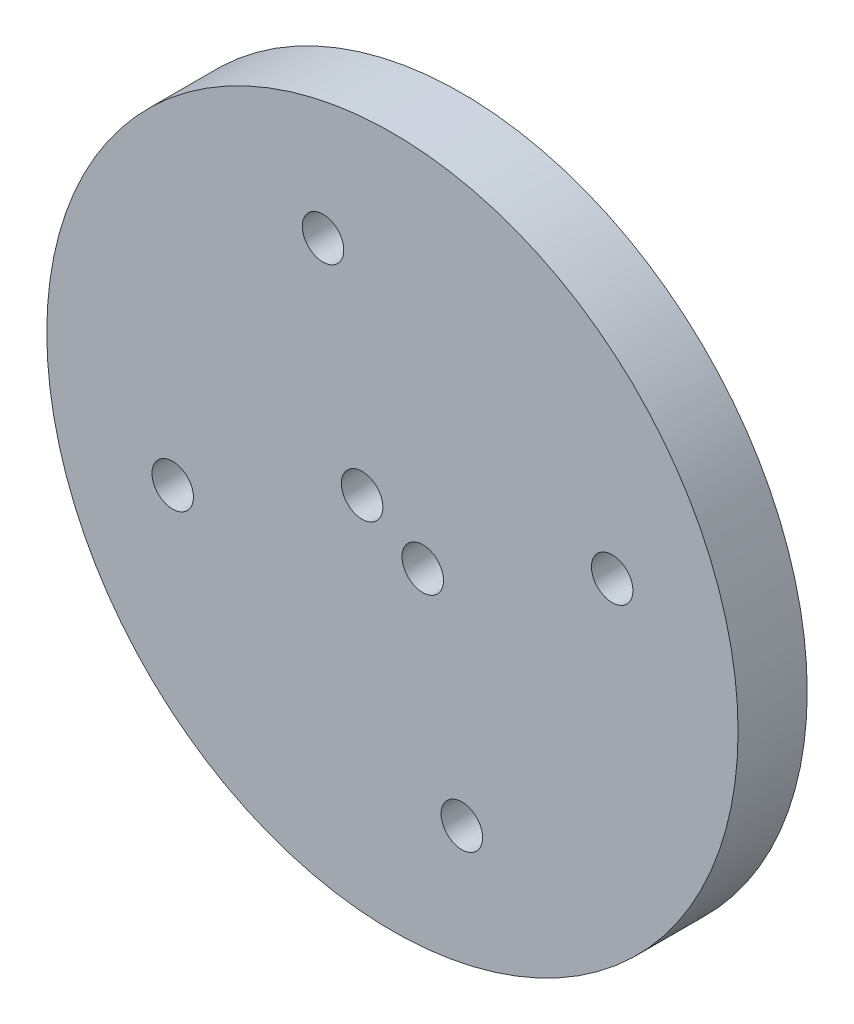
SolidWorks part; units mm, degrees
ref_plane "Front Plane" through (0, 0, 0) normal (0, 0, 1) x (1, 0, 0)
ref_plane "Top Plane" through (0, 0, 0) normal (0, 1, 0) x (1, 0, 0)
ref_plane "Right Plane" through (0, 0, 0) normal (1, 0, 0) x (0, 0, -1)
sketch "Sketch1" plane through (0, 0, 0) normal (0, 0, 1) x (1, 0, 0)
  circle A0 centre (0, 0) radius 15
  point P5 (0, 0)
  point P22 (0, 0)
extrude "Boss-Extrude1" add sketch "Sketch1" along normal blind 3
sketch "Sketch2" plane through (0, 0, 0) normal (0, 0, -1) x (-1, 0, 0)
  line L0 (0, 0) -> (-3.0112, -9.5359) construction
  line L1 (1.316, 0.7198) -> (-1.316, -0.7198)
  circle A0 centre (-3.0112, -9.5359) radius 0.9
  circle A1 centre (-9.5359, 3.0112) radius 0.9
  circle A2 centre (3.0112, 9.5359) radius 0.9
  circle A3 centre (9.5359, -3.0112) radius 0.9
  circle A5 centre (-1.316, -0.7198) radius 0.9
  circle A6 centre (1.316, 0.7198) radius 0.9
  point P13 (0, 0)
  point P14 (0, 0)
  point P16 (0, 0)
  dimension "D2" = 4
  dimension "D3" = 3
  dimension "D1" = 10
extrude "Cut-Extrude1" cut sketch "Sketch2" against normal blind 3
